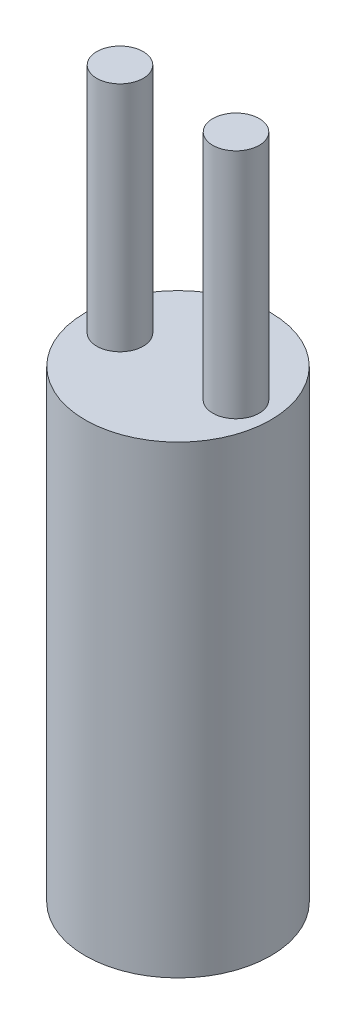
SolidWorks part; units mm, degrees
ref_plane "前视基准面" through (0, 0, 0) normal (0, 0, 1) x (1, 0, 0)
ref_plane "上视基准面" through (0, 0, 0) normal (0, 1, 0) x (1, 0, 0)
ref_plane "右视基准面" through (0, 0, 0) normal (1, 0, 0) x (0, 0, -1)
other "Configuration Table"
sketch "草图1" plane through (0, 0, 0) normal (0, 1, 0) x (1, 0, 0)
  circle A0 centre (0, 0) radius 4
  dimension "D1" = 8
extrude "凸台-拉伸1" add sketch "草图1" along normal blind 20
sketch "草图2" plane through (0, 20, 0) normal (0, 1, 0) x (1, 0, 0)
  circle A0 centre (-2.5, 0) radius 1
  dimension "D1" = 2
  dimension "D2" = 2.5
extrude "凸台-拉伸2" add sketch "草图2" along normal blind 10
mirror "镜向1" about plane through (0, 0, 0) normal (1, 0, 0) of "凸台-拉伸2"
sketch "草图3" plane through (0, 0, 0) normal (0, 1, 0) x (1, 0, 0)
  point P0 (0, 0)
sketch "草图4" plane through (0, 0, 0) normal (0, -1, 0) x (1, 0, 0)
  line L0 (0, 0.5) -> (0, -0.5)
  arc A0 (0, 0.5) -> (0, -0.5) centre (0, 0) ccw
  dimension "D1" = 1
revolve "旋转1" add sketch "草图4" angle 360 about L0
